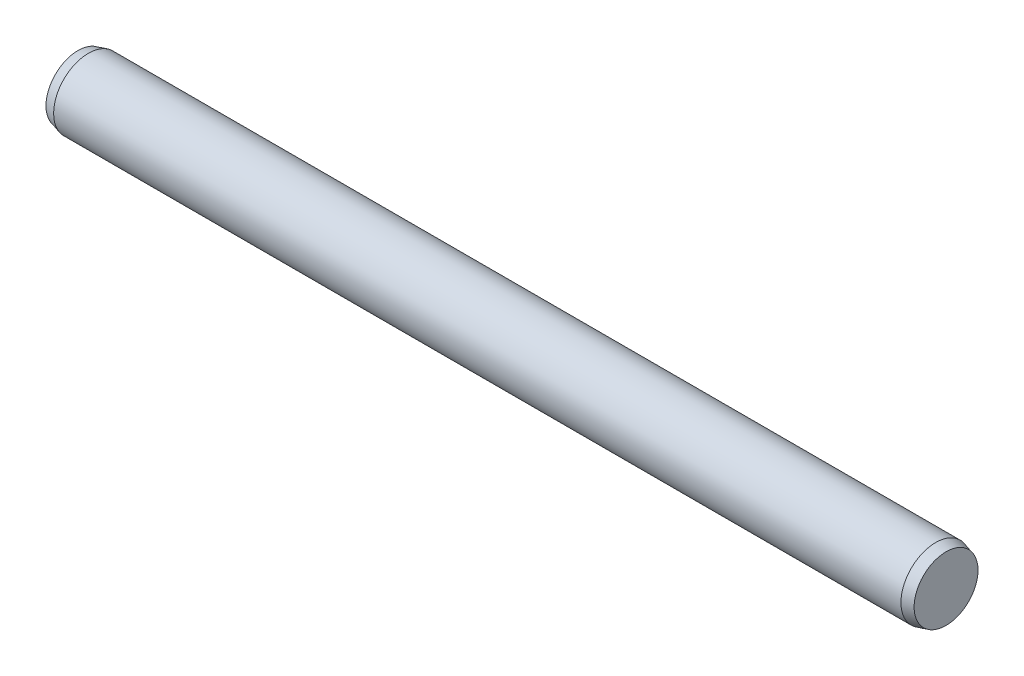
SolidWorks part; units mm, degrees
ref_plane "Front Plane" through (0, 0, 0) normal (0, 0, 1) x (1, 0, 0)
ref_plane "Top Plane" through (0, 0, 0) normal (0, 1, 0) x (1, 0, 0)
ref_plane "Right Plane" through (0, 0, 0) normal (1, 0, 0) x (0, 0, -1)
sketch "Sketch1" plane through (0, 0, 0) normal (0, 0, 1) x (1, 0, 0)
  line L0 (-4.88, 0) -> (4.88, 0) construction
  line L1 (4.88, 0.4) -> (4.88, -0.4) construction
  line L2 (-4.88, 0.4) -> (-4.88, -0.4) construction
  line L3 (5, 0.4) -> (5, -0.4) construction
  line L4 (-5, 0.4) -> (-5, -0.4) construction
  line L5 (-4.88, 0) -> (-5, 0) construction
  line L6 (4.88, 0) -> (5, 0) construction
  dimension "Dia" = 0.8
  dimension "C" = 0.12
  dimension "D1" = 0.12
  dimension "Length" = 10
sketch "Sketch2" plane through (0, 0, 0) normal (1, 0, 0) x (0, 0, -1)
  circle A0 centre (0, 0) radius 0.4
extrude "Extrude1" add sketch "Sketch2" against normal up to vertex (4.88 mm away) and the other way up to vertex (4.88 mm away) up to point (-4.88, 0.4, 0) other way up to point (4.88, 0.4, 0)
sketch "Sketch3" plane through (4.88, 0, 0) normal (1, 0, 0) x (0, 0, -1)
  circle A1 centre (0, 0) radius 0.4
  circle A2 centre (0, 0) radius 0.4
  dimension "D1" = 0
extrude "Extrude2" add sketch "Sketch3" along normal up to vertex (0.12 mm away) draft 15 up to point (5, 0, 0)
sketch "Sketch4" plane through (-4.88, 0, 0) normal (-1, 0, 0) x (0, 0, 1)
  circle A1 centre (0, 0) radius 0.4
  circle A2 centre (0, 0) radius 0.4
  dimension "D1" = 0
extrude "Extrude3" add sketch "Sketch4" along normal up to vertex (0.12 mm away) draft 15 up to point (-5, 0, 0)
equation "\"D1@Sketch1\" = \"C@Sketch1\""
